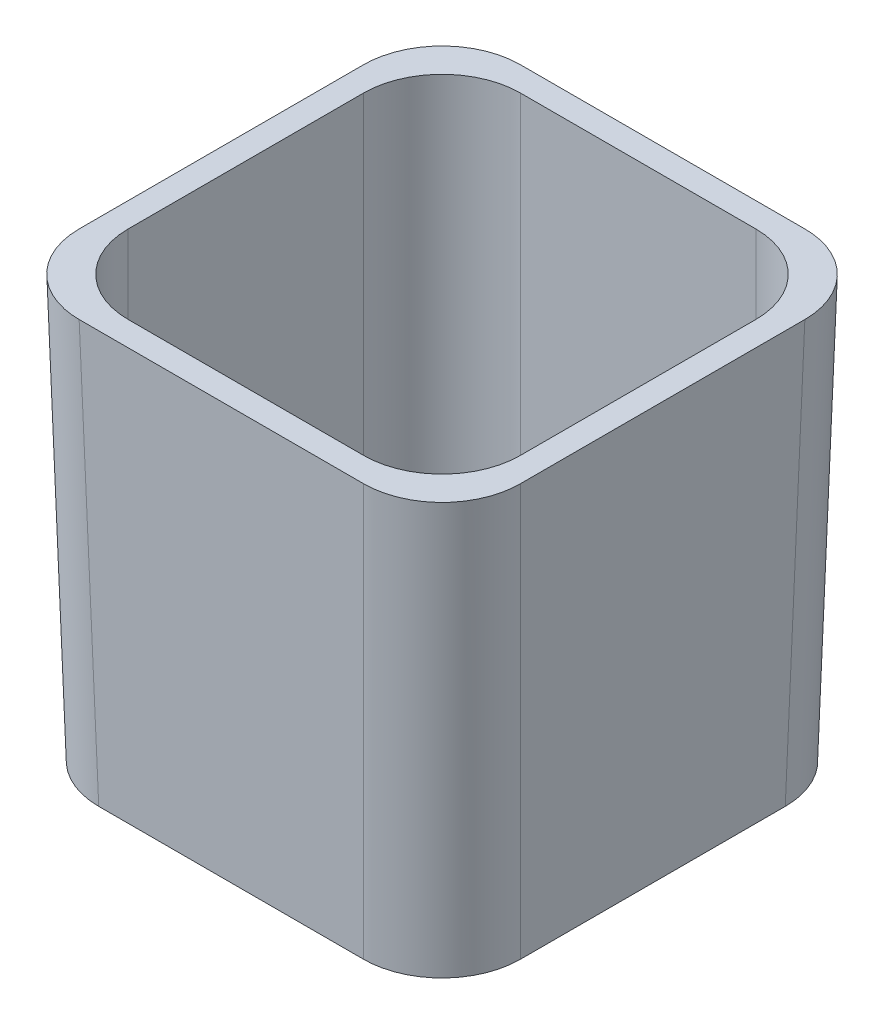
SolidWorks part; units mm, degrees
material "Glass"
ref_plane "Front Plane" through (0, 0, 0) normal (0, 0, 1) x (1, 0, 0)
ref_plane "Top Plane" through (0, 0, 0) normal (0, 1, 0) x (1, 0, 0)
ref_plane "Right Plane" through (0, 0, 0) normal (1, 0, 0) x (0, 0, -1)
sketch "Sketch2" plane through (0, 0, 0) normal (0, 1, 0) x (1, 0, 0)
  line L1 (0, 0) -> (86, 0)
  line L2 (0, 0) -> (0, 86)
  line L3 (0, 86) -> (86, 86)
  line L4 (86, 0) -> (86, 86)
ref_plane "Plane1" through (0, 0, -86) normal (0, 0, -1) x (-1, 0, 0)
sketch "Sketch3" plane through (0, 0, -86) normal (0, 0, -1) x (-1, 0, 0)
  line L0 (0, 0) -> (0, 86) construction
ref_plane "Plane2" through (0, 86, -86) normal (0, 1, 0) x (1, 0, 0)
sketch "Sketch4" plane through (0, 86, -86) normal (0, 1, 0) x (1, 0, 0)
  line L0 (88, 2) -> (88, -88)
  line L1 (88, 2) -> (-2, 2)
  line L2 (88, -88) -> (-2, -88)
  line L3 (-2, 2) -> (-2, -88)
  line L4 (88, 2) -> (-2, -88) construction
  line L5 (88, -88) -> (-2, 2) construction
  point P1 (43, -43)
loft "Loft1" add profiles "Sketch4", "Sketch2"
sketch "Sketch5" plane through (0, 86, 0) normal (0, 1, 0) x (1, 0, 0)
  line L0 (83, 83) -> (83, 3)
  line L1 (83, 83) -> (3, 83)
  line L2 (83, 3) -> (3, 3)
  line L3 (3, 83) -> (3, 3)
  line L4 (83, 83) -> (3, 3) construction
  line L5 (83, 3) -> (3, 83) construction
  point P1 (43, 43)
extrude "Cut-Extrude1" cut sketch "Sketch5" against normal blind 81
fillet "Fillet1" radius 16 8 edges at (83, 45.5, -83) (83, 45.5, -3) (3, 45.5, -3) (3, 45.5, -83)
